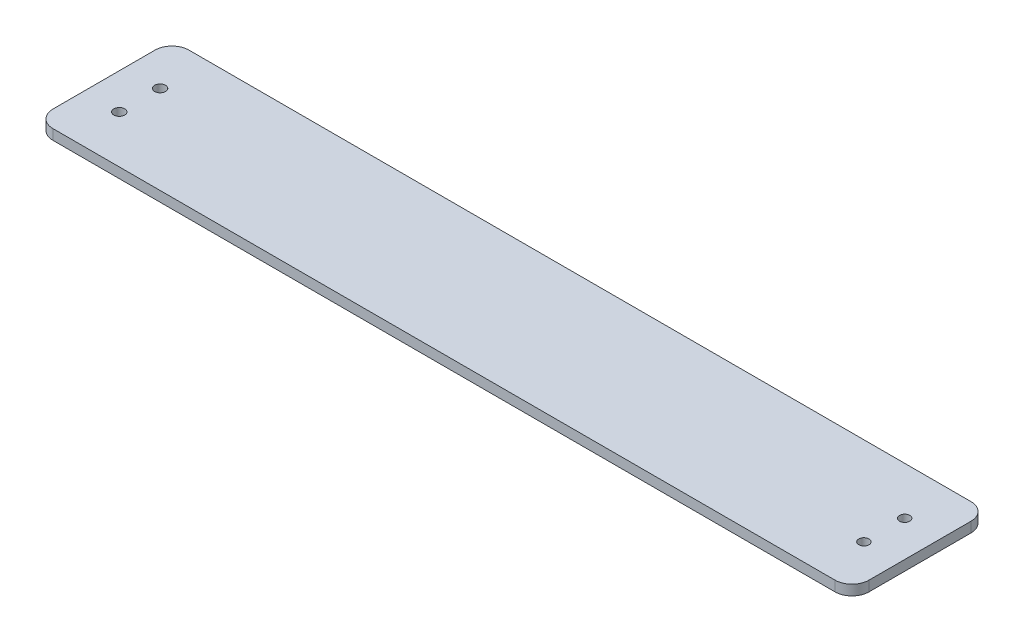
SolidWorks part; units mm, degrees
ref_plane "前视基准面" through (0, 0, 0) normal (0, 0, 1) x (1, 0, 0)
ref_plane "上视基准面" through (0, 0, 0) normal (0, 1, 0) x (1, 0, 0)
ref_plane "右视基准面" through (0, 0, 0) normal (1, 0, 0) x (0, 0, -1)
sketch "草图1" plane through (0, 0, 0) normal (0, 1, 0) x (1, 0, 0)
  line L0 (-115, 0) -> (115, 0)
  line L1 (-120, -35) -> (-120, -5)
  line L2 (115, -40) -> (-115, -40)
  line L3 (120, -5) -> (120, -35)
  circle A0 centre (-109.5, -26) radius 1.6
  circle A1 centre (109.5, -14) radius 1.5
  arc A2 (120, -5) -> (115, 0) centre (115, -5) ccw
  arc A3 (-115, 0) -> (-120, -5) centre (-115, -5) ccw
  arc A4 (-120, -35) -> (-115, -40) centre (-115, -35) ccw
  arc A5 (115, -40) -> (120, -35) centre (115, -35) ccw
  circle A6 centre (109.5, -26) radius 1.5
  circle A7 centre (-109.5, -14) radius 1.6
  dimension "D1" = 240
extrude "凸台-拉伸1" add sketch "草图1" along normal blind 3
